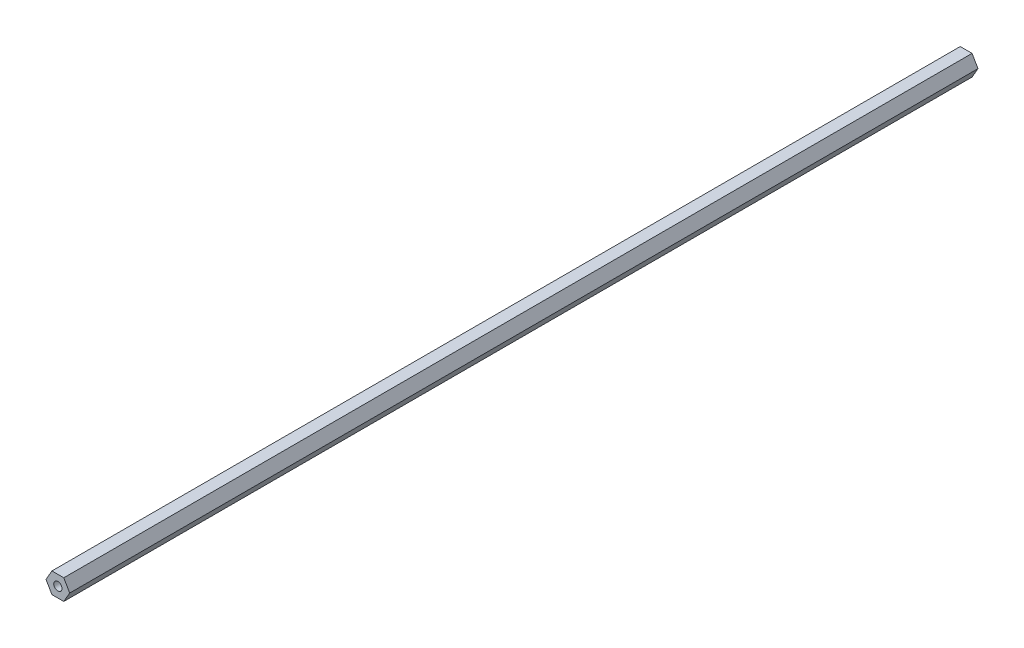
SolidWorks part; units mm, degrees
material "Plain Carbon Steel"
ref_plane "Front Plane" through (0, 0, 0) normal (0, 0, 1) x (1, 0, 0)
ref_plane "Top Plane" through (0, 0, 0) normal (0, 1, 0) x (1, 0, 0)
ref_plane "Right Plane" through (0, 0, 0) normal (1, 0, 0) x (0, 0, -1)
sketch "Sketch1" plane through (0, 0, 0) normal (0, 0, 1) x (1, 0, 0)
  line L1 (7.3323, 0) -> (3.6662, 6.35)
  line L2 (3.6662, 6.35) -> (-3.6662, 6.35)
  line L3 (-3.6662, 6.35) -> (-7.3323, 0)
  line L4 (-7.3323, 0) -> (-3.6662, -6.35)
  line L5 (-3.6662, -6.35) -> (3.6662, -6.35)
  line L6 (3.6662, -6.35) -> (7.3323, 0)
  circle A0 centre (0, 0) radius 6.35 construction
  dimension "D1" = 12.7
extrude "Boss-Extrude1" add sketch "Sketch1" along normal blind 561.975
hole_wizard "1/4-20 Tapped Hole1" positions "Sketch2" profile "Sketch3" tap size "1/4-20" standard "ANSI Inch"
sketch "Sketch2" plane through (0, 0, 561.975) normal (0, 0, 1) x (1, 0, 0)
  point P0 (0, 0)
sketch "Sketch3" plane through (0, 0, 561.975) normal (1, 0, 0) x (0, -1, 0)
  line L0 (0, 0) -> (0, 18.0438)
  line L1 (0, 18.0438) -> (2.5527, 16.51)
  line L2 (2.5527, 16.51) -> (2.5527, 0)
  line L5 (2.5527, 0) -> (0, 0)
  line L10 (0, 18.0438) -> (-2.5527, 16.51) construction
  line L11 (0, -6.35) -> (0, 107.95) construction
  dimension "Tap Drill Dia." = 5.1054
  dimension "Tap Drill Depth" = 16.51
  dimension "Drill Angle" = 118
cosmetic thread "Hole Thread1" parameters "D1"=12.7, "D2"=6.35
hole_wizard "1/4-20 Tapped Hole2" positions "Sketch4" profile "Sketch5" tap size "1/4-20" standard "ANSI Inch"
sketch "Sketch4" plane through (0, 0, 0) normal (0, 0, -1) x (-1, 0, 0)
  point P0 (0, 0)
sketch "Sketch5" plane through (0, 0, 0) normal (1, 0, 0) x (0, 1, 0)
  line L0 (0, 0) -> (0, 18.0438)
  line L1 (0, 18.0438) -> (2.5527, 16.51)
  line L2 (2.5527, 16.51) -> (2.5527, 0)
  line L5 (2.5527, 0) -> (0, 0)
  line L10 (0, 18.0438) -> (-2.5527, 16.51) construction
  line L11 (0, -6.35) -> (0, 107.95) construction
  dimension "Tap Drill Dia." = 5.1054
  dimension "Tap Drill Depth" = 16.51
  dimension "Drill Angle" = 118
cosmetic thread "Hole Thread2"
